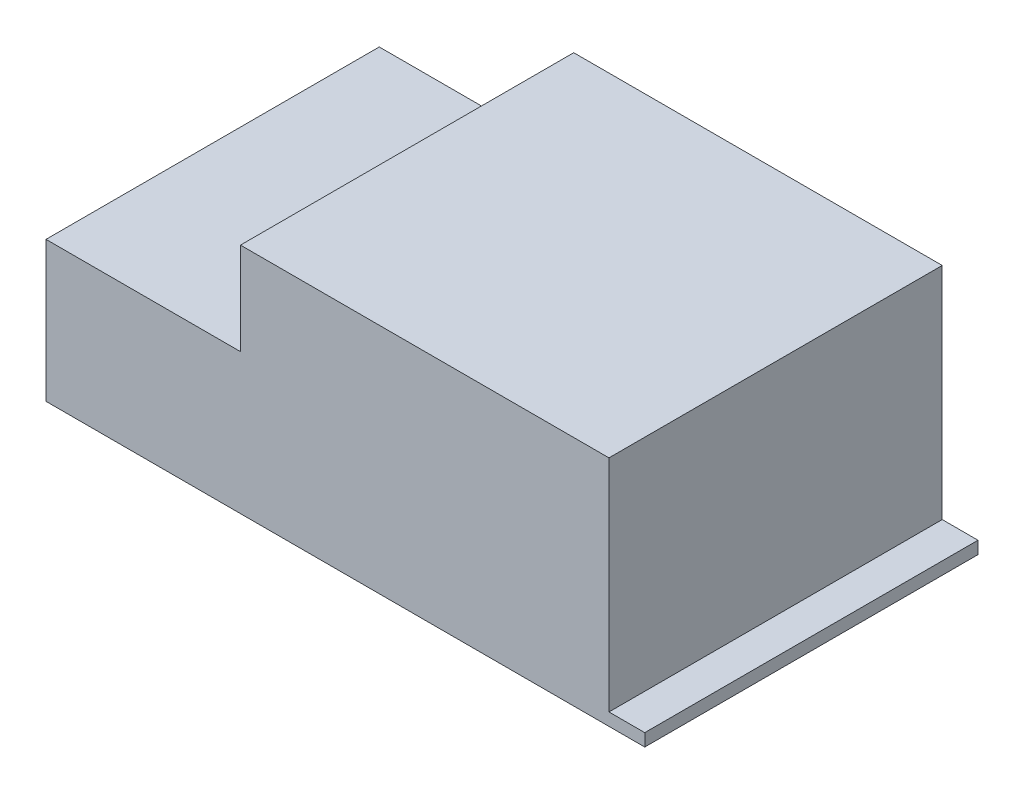
SolidWorks part; units mm, degrees
ref_plane "Front Plane" through (0, 0, 0) normal (0, 0, 1) x (1, 0, 0)
ref_plane "Top Plane" through (0, 0, 0) normal (0, 1, 0) x (1, 0, 0)
ref_plane "Right Plane" through (0, 0, 0) normal (1, 0, 0) x (0, 0, -1)
sketch "Sketch1" plane through (0, 0, 0) normal (0, 0, 1) x (1, 0, 0)
  line L0 (97.0495, 44.9712) -> (97.0495, 47.9712)
  line L1 (88.4596, 100.803) -> (0, 100.803)
  line L2 (0, 100.803) -> (0, 78.6557)
  line L3 (0, 78.6557) -> (-46.6872, 78.6557)
  line L4 (97.0495, 44.9712) -> (-46.6872, 44.9712)
  line L6 (-46.6872, 78.6557) -> (-46.6872, 44.9712)
  line L7 (88.4596, 47.9712) -> (88.4596, 100.803)
  line L9 (97.0495, 47.9712) -> (88.4596, 47.9712)
  dimension "D1" = 3
extrude "Boss-Extrude1" add sketch "Sketch1" along normal up to surface (70.9582 mm away) and the other way up to surface (9.0418 mm away)
sketch "Sketch3" plane through (-46.6872, 0, 0) normal (-1, 0, 0) x (0, 0, 1)
  circle A0 centre (32.4214, 59.3229) radius 5.5154
extrude "Cut-Extrude1" cut sketch "Sketch3" against normal blind 22
sketch "Sketch4" plane through (0, 44.9712, 0) normal (0, -1, 0) x (-1, 0, 0)
  line L1 (-12.0495, -68.6561) -> (44.7411, -68.6561)
  line L2 (-12.0495, -68.6561) -> (-12.0495, 7.2877)
  line L3 (-12.0495, 7.2877) -> (44.7411, 7.2877)
  line L4 (44.7411, -68.6561) -> (44.7411, 7.2877)
  dimension "D1" = 75.9438
extrude "Cut-Extrude2" cut sketch "Sketch4" against normal blind 31
sketch "Sketch5" plane through (0, 44.9712, 0) normal (0, -1, 0) x (-1, 0, 0)
  line L0 (-12.0495, 7.2877) -> (-12.0495, -68.6561) construction
  line L1 (-12.0495, -68.6561) -> (-87.0495, -68.6561)
  line L2 (-12.0495, -68.6561) -> (-12.0495, 7.2877)
  line L3 (-12.0495, 7.2877) -> (-87.0495, 7.2877)
  line L4 (-87.0495, -68.6561) -> (-87.0495, 7.2877)
  line L5 (-12.0495, -68.6561) -> (44.7411, -68.6561) construction
  dimension "D1" = 75.9438
  dimension "D2" = 75
extrude "Cut-Extrude3" cut sketch "Sketch5" against normal blind 51
